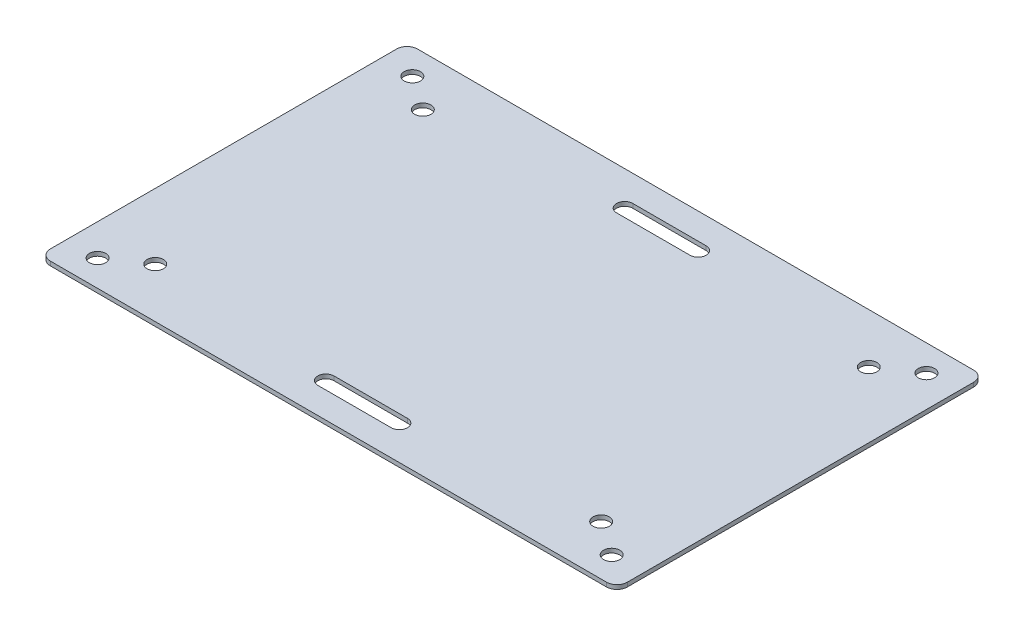
SolidWorks part; units mm, degrees
ref_plane "前视基准面" through (0, 0, 0) normal (0, 0, 1) x (1, 0, 0)
ref_plane "上视基准面" through (0, 0, 0) normal (0, 1, 0) x (1, 0, 0)
ref_plane "右视基准面" through (0, 0, 0) normal (1, 0, 0) x (0, 0, -1)
other "Configuration Table"
sketch "草图1" plane through (0, 0, 0) normal (0, 1, 0) x (1, 0, 0)
  line L0 (0, 0) -> (0, -50000) construction
  line L1 (-55, 35) -> (55, 35)
  line L2 (-55, 35) -> (-55, -35)
  line L3 (-55, -35) -> (55, -35)
  line L4 (55, 35) -> (55, -35)
  line L5 (-55, 35) -> (55, -35) construction
  line L6 (-55, -35) -> (55, 35) construction
  line L7 (0, 0) -> (-50000, 0) construction
  line L8 (-7, 30.0234) -> (7, 30.0234)
  line L9 (7, 26.9234) -> (-7, 26.9234)
  line L10 (7, -26.9234) -> (-7, -26.9234)
  line L11 (-7, -30.0234) -> (7, -30.0234)
  circle A0 centre (-49, 30) radius 1.55
  circle A1 centre (49, 30) radius 1.55
  circle A2 centre (49, -30) radius 1.55
  circle A3 centre (-49, -30) radius 1.55
  circle A4 centre (-42.5, 25.5) radius 1.55
  circle A5 centre (42.5, 25.5) radius 1.55
  circle A6 centre (42.5, -25.5) radius 1.55
  circle A7 centre (-42.5, -25.5) radius 1.55
  arc A8 (-7, 26.9234) -> (-7, 30.0234) centre (-7, 28.4734) cw
  arc A9 (7, 26.9234) -> (7, 30.0234) centre (7, 28.4734) ccw
  arc A10 (7, -26.9234) -> (7, -30.0234) centre (7, -28.4734) cw
  arc A11 (-7, -26.9234) -> (-7, -30.0234) centre (-7, -28.4734) ccw
  point P0 (0, 0)
  point P26 (-7, 30.0234)
  point P27 (7, 30.0234)
  point P28 (-7, 26.9234)
  point P29 (7, 26.9234)
  dimension "D3" = 3.1
  dimension "D5" = 3.1
  dimension "D1" = 110
  dimension "D2" = 70
  dimension "D4" = 60
  dimension "D6" = 85
  dimension "D7" = 51
  dimension "D8" = 98
  dimension "D9" = 3.1
  dimension "D10" = 14
extrude "凸台-拉伸1" add sketch "草图1" along normal blind 0.8
fillet "圆角1" radius 2 1 edges at (55, 0.4, -35)
fillet "圆角2" radius 2 1 edges at (-55, 0.4, -35)
fillet "圆角3" radius 2 1 edges at (-55, 0.4, 35)
fillet "圆角4" radius 2 1 edges at (55, 0.4, 35)
